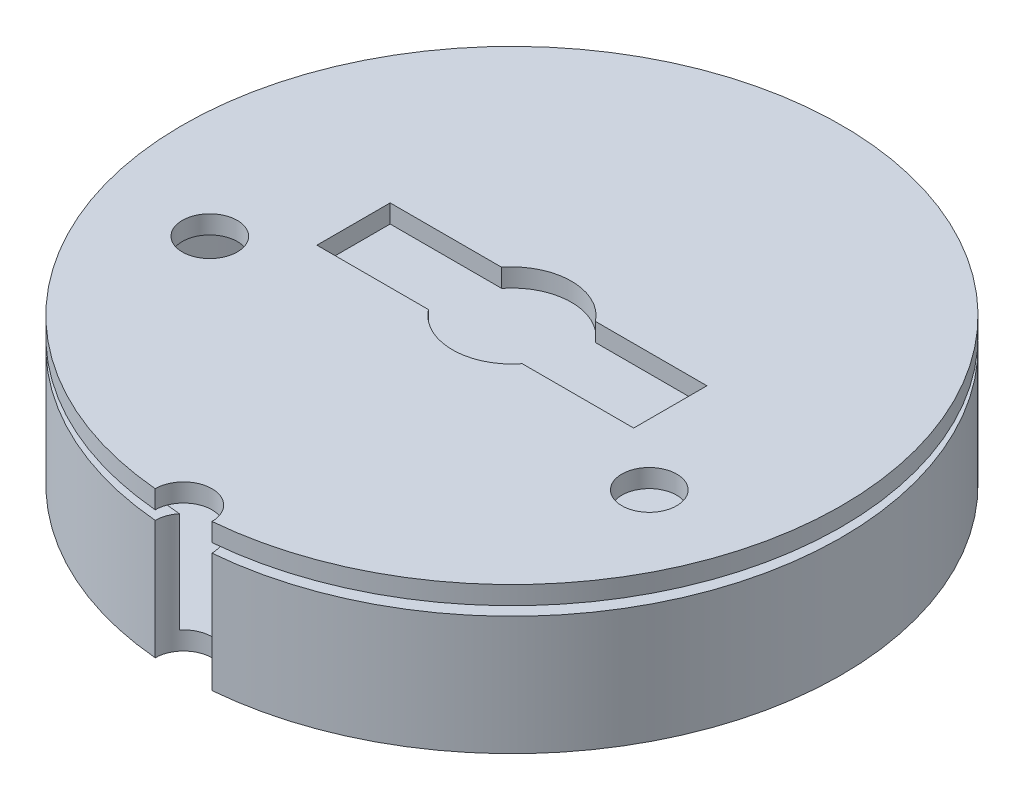
SolidWorks part; units mm, degrees
ref_plane "Front Plane" through (0, 0, 0) normal (0, 0, 1) x (1, 0, 0)
ref_plane "Top Plane" through (0, 0, 0) normal (0, 1, 0) x (1, 0, 0)
ref_plane "Right Plane" through (0, 0, 0) normal (1, 0, 0) x (0, 0, -1)
sketch "Sketch1" plane through (0, 0, 0) normal (0, 1, 0) x (1, 0, 0)
  line L2 (0, 0) -> (0, -41.6132) construction
  arc A0 (3.937, -45.5502) -> (-3.937, -45.5502) centre (0, 0) ccw
  circle A2 centre (0, 0) radius 5.588
  arc A3 (3.937, -45.5502) -> (-3.937, -45.5502) centre (0, -45.5502) ccw
  dimension "D1" = 11.176
  dimension "D2" = 91.44
  dimension "D3" = 7.874
extrude "Boss-Extrude1" add sketch "Sketch1" along normal blind 20.32
sketch "Sketch2" plane through (0, 0, 0) normal (0, 1, 0) x (1, 0, 0)
  line L0 (0, 0) -> (0, 45.72) construction
  line L1 (-45.72, 0) -> (45.72, 0) construction
  line L2 (27.1131, 20.4197) -> (47.5785, 20.4197)
  line L4 (47.5785, -16.6643) -> (47.5785, 20.4197)
  line L5 (-27.1131, 20.4197) -> (-54.2576, 20.4197)
  line L7 (-54.2576, -16.6643) -> (-54.2576, 20.4197)
  line L8 (-27.1131, -16.6643) -> (27.1131, -16.6643)
  line L9 (47.5785, -16.6643) -> (47.5785, -51.6601)
  line L10 (47.5785, -51.6601) -> (-54.2576, -51.6601)
  line L11 (-54.2576, -51.6601) -> (-54.2576, -16.6643)
  circle A0 centre (0, 0) radius 45.72 construction
  circle A1 centre (0, 27.178) radius 18.542 construction
  arc A2 (27.1131, 20.4197) -> (27.1131, -16.6643) centre (27.1131, 1.8777) ccw
  arc A3 (-27.1131, 20.4197) -> (-27.1131, -16.6643) centre (-27.1131, 1.8777) cw
  dimension "D1" = 37.084
  dimension "D2" = 37.084
sketch "Sketch4" plane through (0, 0, 0) normal (0, 1, 0) x (1, 0, 0)
  line L0 (-17.272, 27.178) -> (-17.272, 49.4663)
  line L1 (17.272, 27.178) -> (17.272, 49.4663)
  line L2 (17.272, 49.4663) -> (-17.272, 49.4663)
  arc A0 (-17.272, 27.178) -> (17.272, 27.178) centre (0, 27.178) ccw
  circle A1 centre (0, 27.178) radius 18.542 construction
  dimension "D1" = 1.27
extrude "Cut-Extrude3" [suppressed] cut sketch "Sketch2" along normal blind 10.16
extrude "Cut-Extrude4" [suppressed] cut sketch "Sketch4" along normal blind 10.16 contours L2 L0 A0 L1
sketch "Sketch5" plane through (0, 0, 0) normal (0, 1, 0) x (1, 0, 0)
  circle A0 centre (0, 0) radius 8.255
  dimension "D1" = 16.51
extrude "Cut-Extrude5" cut sketch "Sketch5" along normal blind 47.498 from offset 2.54
sketch "Sketch6" plane through (0, 0, 0) normal (0, 1, 0) x (1, 0, 0)
  circle A0 centre (0, 0) radius 43.18
  arc A1 (3.937, -45.5502) -> (-3.937, -45.5502) centre (0, 0) ccw construction
  circle A2 centre (0, 0) radius 8.1721
  dimension "D1" = 2.54
  dimension "D2" = 16.3441
extrude "Cut-Extrude7" cut sketch "Sketch6" against normal blind 15.24 from offset 17.78 contours A0
sketch "Sketch7" plane through (0, 0, 0) normal (0, 1, 0) x (1, 0, 0)
  line L1 (-21.971, -5.08) -> (21.971, -5.08)
  line L2 (-21.971, -5.08) -> (-21.971, 5.08)
  line L3 (-21.971, 5.08) -> (21.971, 5.08)
  line L4 (21.971, -5.08) -> (21.971, 5.08)
  line L5 (-21.971, -5.08) -> (21.971, 5.08) construction
  line L6 (-21.971, 5.08) -> (21.971, -5.08) construction
  point P0 (0, 0)
  dimension "D1" = 43.942
  dimension "D2" = 10.16
extrude "Cut-Extrude8" cut sketch "Sketch7" along normal blind 28.448 from offset 10.16
sketch "Sketch8" plane through (0, 0, 0) normal (1, 0, 0) x (0, 0, -1)
  line L0 (-52.8354, 17.78) -> (55.7377, 17.78)
  line L1 (55.7377, 17.78) -> (55.7377, 16.51)
  line L2 (55.7377, 16.51) -> (-52.8354, 16.51)
  line L3 (-52.8354, 16.51) -> (-52.8354, 17.78)
  line L5 (45.72, 20.32) -> (-45.5502, 20.32) construction
  dimension "D1" = 2.54
  dimension "D2" = 1.27
extrude "Cut-Extrude9" cut sketch "Sketch8" against normal blind 70.612 and the other way blind 72.898
sketch "Sketch9" plane through (0, 0, 0) normal (0, 1, 0) x (1, 0, 0)
  line L0 (-45.72, 0) -> (45.72, 0) construction
  line L1 (0, 0) -> (0, -51.6601) construction
  line L2 (47.5785, -51.6601) -> (-54.2576, -51.6601) construction
  circle A0 centre (-30.48, -11.43) radius 3.81
  circle A1 centre (30.48, -11.43) radius 3.81
  dimension "D1" = 7.62
  dimension "D2" = 11.43
  dimension "D3" = 30.48
extrude "Cut-Extrude10" cut sketch "Sketch9" along normal blind 39.37
sketch "Sketch10" [suppressed] plane through (0, 0, 0) normal (0, 1, 0) x (1, 0, 0)
  line L0 (-44.5283, -32.8502) -> (-27.178, -32.8502)
  line L1 (-27.178, -32.8502) -> (-27.178, -56.318)
  line L2 (-27.178, -56.318) -> (-44.5283, -32.8502)
  line L3 (0, 0) -> (0, -49.172) construction
  line L4 (27.178, -32.8502) -> (27.178, -56.318)
  line L5 (44.5283, -32.8502) -> (27.178, -32.8502)
  line L6 (27.178, -56.318) -> (44.5283, -32.8502)
  arc A0 (3.937, -45.5502) -> (-3.937, -45.5502) centre (0, 0) ccw construction
  dimension "D1" = 12.7
  dimension "D2" = 27.178
extrude "Cut-Extrude11" [suppressed] cut sketch "Sketch10" along normal blind 31.242 contours L2 L0 L1 | L4 L6 L5
split "Split1" bodies to split 114 115 resulting bodies 112 113
